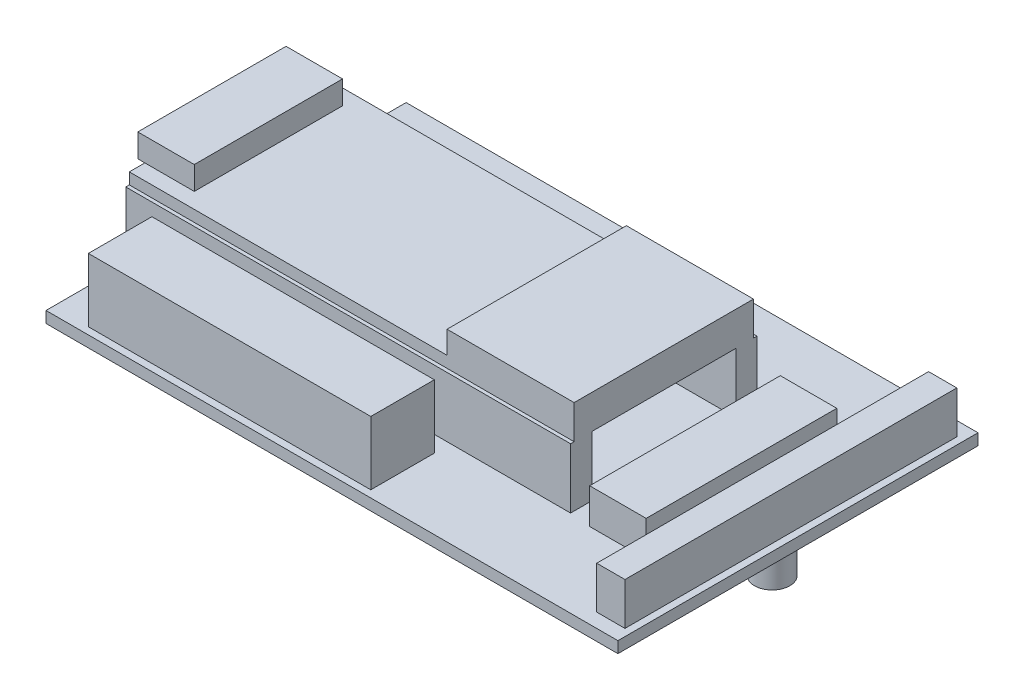
SolidWorks part; units mm, degrees
ref_plane "Front Plane" through (0, 0, 0) normal (0, 0, 1) x (1, 0, 0)
ref_plane "Top Plane" through (0, 0, 0) normal (0, 1, 0) x (1, 0, 0)
ref_plane "Right Plane" through (0, 0, 0) normal (1, 0, 0) x (0, 0, -1)
sketch "SK_P01_Standoff" plane through (0, 0, 0) normal (0, 1, 0) x (1, 0, 0)
  circle A0 centre (-35.85, 0) radius 2.5
extrude "P01_Standoff" add sketch "SK_P01_Standoff" along normal blind 5
sketch "SK_P02_Standoff" plane through (0, 0, 0) normal (0, 1, 0) x (1, 0, 0)
  circle A0 centre (37.85, 0) radius 2.5
extrude "P02_Standoff" add sketch "SK_P02_Standoff" along normal blind 5
sketch "SK_P03_PermaProtohalfsizecarrie" plane through (0, 0, 0) normal (0, 1, 0) x (1, 0, 0)
  line L0 (-39.5, -25.5) -> (41.5, -25.5)
  line L1 (41.5, -25.5) -> (41.5, 25.5)
  line L2 (41.5, 25.5) -> (-39.5, 25.5)
  line L3 (-39.5, 25.5) -> (-39.5, -25.5)
extrude "P03_PermaProtohalfsizecarrie" add sketch "SK_P03_PermaProtohalfsizecarrie" along normal blind 1.6 from offset 5
sketch "SK_P04_Socketrow" plane through (0, 0, 0) normal (0, 1, 0) x (1, 0, 0)
  line L0 (-40.5, 10.2) -> (22.5, 10.2)
  line L1 (22.5, 10.2) -> (22.5, 13.2)
  line L2 (22.5, 13.2) -> (-40.5, 13.2)
  line L3 (-40.5, 13.2) -> (-40.5, 10.2)
extrude "P04_Socketrow" add sketch "SK_P04_Socketrow" along normal blind 8.5 from offset 6.6
sketch "SK_P05_Socketrow" plane through (0, 0, 0) normal (0, 1, 0) x (1, 0, 0)
  line L0 (-40.5, -13.2) -> (22.5, -13.2)
  line L1 (22.5, -13.2) -> (22.5, -10.2)
  line L2 (22.5, -10.2) -> (-40.5, -10.2)
  line L3 (-40.5, -10.2) -> (-40.5, -13.2)
extrude "P05_Socketrow" add sketch "SK_P05_Socketrow" along normal blind 8.5 from offset 6.6
sketch "SK_P06_DevKitC1" plane through (0, 0, 0) normal (0, 1, 0) x (1, 0, 0)
  line L0 (-40.5, -12.7) -> (22.5, -12.7)
  line L1 (22.5, -12.7) -> (22.5, 12.7)
  line L2 (22.5, 12.7) -> (-40.5, 12.7)
  line L3 (-40.5, 12.7) -> (-40.5, -12.7)
extrude "P06_DevKitC1" add sketch "SK_P06_DevKitC1" along normal blind 1.6 from offset 15.1
sketch "SK_P07_WROOM2module" plane through (0, 0, 0) normal (0, 1, 0) x (1, 0, 0)
  line L0 (4.5, -12.7) -> (22.5, -12.7)
  line L1 (22.5, -12.7) -> (22.5, 12.7)
  line L2 (22.5, 12.7) -> (4.5, 12.7)
  line L3 (4.5, 12.7) -> (4.5, -12.7)
extrude "P07_WROOM2module" add sketch "SK_P07_WROOM2module" along normal blind 3.2 from offset 16.7
sketch "SK_P08_USBCx2" plane through (0, 0, 0) normal (0, 1, 0) x (1, 0, 0)
  line L0 (-41.5, -10.5) -> (-33.5, -10.5)
  line L1 (-33.5, -10.5) -> (-33.5, 10.5)
  line L2 (-33.5, 10.5) -> (-41.5, 10.5)
  line L3 (-41.5, 10.5) -> (-41.5, -10.5)
extrude "P08_USBCx2" add sketch "SK_P08_USBCx2" along normal blind 3.3 from offset 16.7
sketch "SK_P09_74LVC244" plane through (0, 0, 0) normal (0, 1, 0) x (1, 0, 0)
  line L0 (25.5, -13.5) -> (33.5, -13.5)
  line L1 (33.5, -13.5) -> (33.5, 13.5)
  line L2 (33.5, 13.5) -> (25.5, 13.5)
  line L3 (25.5, 13.5) -> (25.5, -13.5)
extrude "P09_74LVC244" add sketch "SK_P09_74LVC244" along normal blind 5 from offset 6.6
sketch "SK_P10_JSTXHheadersvertical" plane through (0, 0, 0) normal (0, 1, 0) x (1, 0, 0)
  line L0 (36.5, -23.5) -> (40.5, -23.5)
  line L1 (40.5, -23.5) -> (40.5, 23.5)
  line L2 (40.5, 23.5) -> (36.5, 23.5)
  line L3 (36.5, 23.5) -> (36.5, -23.5)
extrude "P10_JSTXHheadersvertical" add sketch "SK_P10_JSTXHheadersvertical" along normal blind 6 from offset 6.6
sketch "SK_P11_2x12boxheaderdecksignals" plane through (0, 0, 0) normal (0, 1, 0) x (1, 0, 0)
  line L0 (-34.5, -24.5) -> (5.5, -24.5)
  line L1 (5.5, -24.5) -> (5.5, -15.5)
  line L2 (5.5, -15.5) -> (-34.5, -15.5)
  line L3 (-34.5, -15.5) -> (-34.5, -24.5)
extrude "P11_2x12boxheaderdecksignals" add sketch "SK_P11_2x12boxheaderdecksignals" along normal blind 9 from offset 6.6
